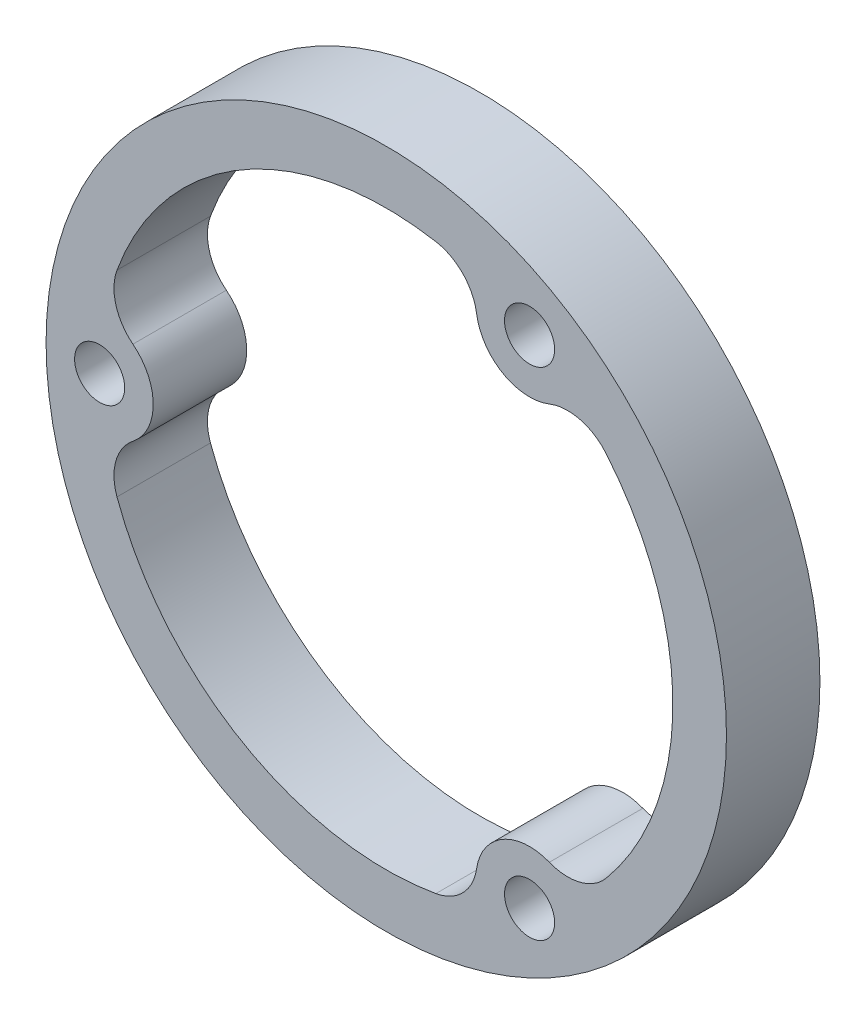
SolidWorks part; units mm, degrees
material "6061-T6 (SS)"
ref_plane "Front Plane" through (0, 0, 0) normal (0, 0, 1) x (1, 0, 0)
ref_plane "Top Plane" through (0, 0, 0) normal (0, 1, 0) x (1, 0, 0)
ref_plane "Right Plane" through (0, 0, 0) normal (1, 0, 0) x (0, 0, -1)
sketch "Sketch1" plane through (0, 0, 0) normal (0, 0, 1) x (1, 0, 0)
  arc A0 (19.0584, -22.136) -> (19.0584, 22.136) centre (0, 0) ccw
  circle A1 centre (0, 0) radius 34.671
  arc A4 (-28.6995, -5.4371) -> (-28.6995, 5.4371) centre (-29.21, 0) ccw
  arc A5 (9.6411, 27.5731) -> (19.0584, 22.136) centre (14.605, 25.2966) ccw
  arc A6 (19.0584, -22.136) -> (9.6411, -27.5731) centre (14.605, -25.2966) ccw
  arc A7 (9.6411, 27.5731) -> (-28.6995, 5.4371) centre (0, 0) ccw
  arc A8 (-28.6995, -5.4371) -> (9.6411, -27.5731) centre (0, 0) ccw
  point P14 (0, 0)
  dimension "D1" = 58.42
  dimension "D2" = 69.342
  dimension "D4" = 3
  dimension "D3" = 30
  dimension "D5" = 120
  dimension "D6" = 120
extrude "Boss-Extrude1" add sketch "Sketch1" along normal blind 9.525
fillet "Fillet1" radius 5.08 6 edges at (9.6411, 27.5731, 4.7625) (19.0584, 22.136, 4.7625) (9.6411, -27.5731, 4.7625) (19.0584, -22.136, 4.7625) (-28.6995, 5.4371, 4.7625) (-28.6995, -5.4371, 4.7625)
hole_wizard "#10 Clearance Hole1" positions "Sketch2" profile "Sketch3" hole size "#10" standard "ANSI Inch" end condition through all
sketch "Sketch2" plane through (0, 0, 0) normal (0, 0, -1) x (-1, 0, 0)
  point P0 (-14.605, 25.2966)
  point P3 (29.21, 0)
  point P6 (-14.605, -25.2966)
sketch "Sketch3" plane through (14.605, 25.2966, 0) normal (1, 0, 0) x (0, 1, 0)
  line L0 (0, 0) -> (0, 9.525)
  line L1 (0, 9.525) -> (2.5527, 9.525)
  line L2 (2.5527, 9.525) -> (2.5527, 0)
  line L5 (2.5527, 0) -> (0, 0)
  line L11 (0, -6.35) -> (0, 107.95) construction
  dimension "Thru Hole Dia." = 5.1054
  dimension "Thru Hole Depth" = 9.525
